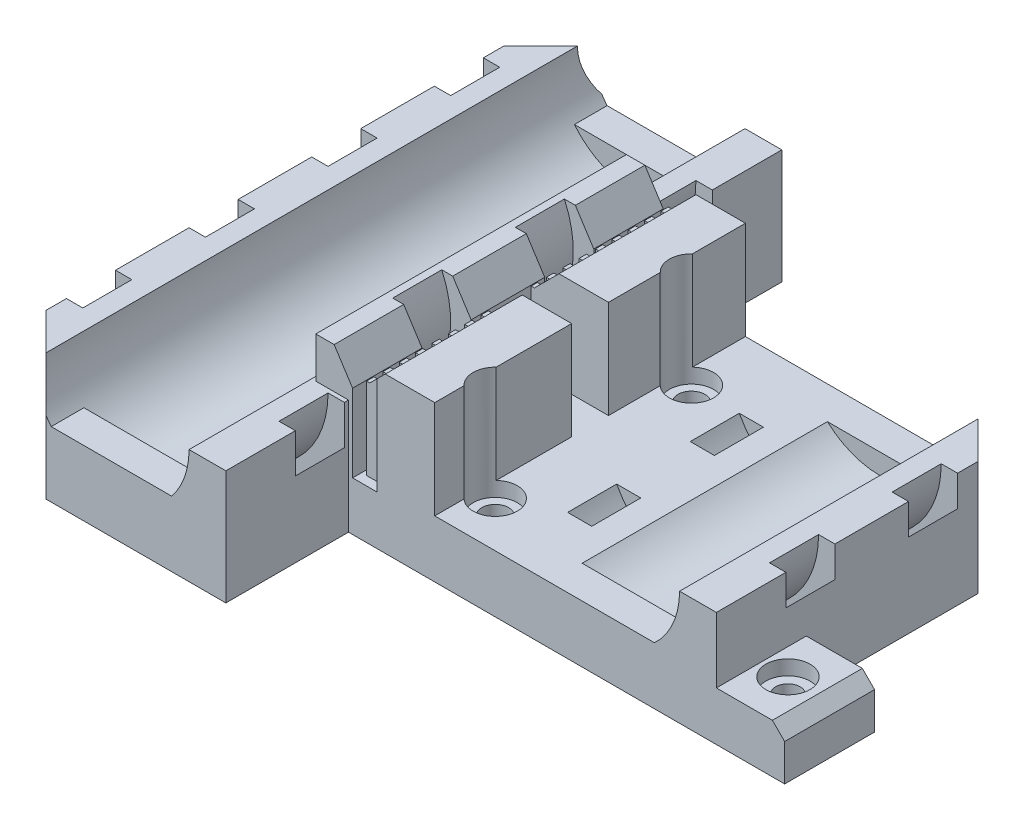
SolidWorks part; units mm, degrees
ref_plane "Front Plane" through (0, 0, 0) normal (0, 0, 1) x (1, 0, 0)
ref_plane "Top Plane" through (0, 0, 0) normal (0, 1, 0) x (1, 0, 0)
ref_plane "Right Plane" through (0, 0, 0) normal (1, 0, 0) x (0, 0, -1)
sketch "Sketch1" plane through (0, 0, 0) normal (0, 1, 0) x (1, 0, 0)
  line L0 (0.3879, -8.2154) -> (0.3879, 6.7846)
  line L1 (-27.6121, -8.2154) -> (0.3879, -8.2154)
  line L2 (-27.6121, -8.2154) -> (-27.6121, 59.7846)
  line L3 (-27.6121, 59.7846) -> (0.3879, 59.7846)
  line L4 (0.3879, 6.7846) -> (53.7379, 6.7846)
  line L5 (53.7379, 6.7846) -> (53.7379, 17.7846)
  line L6 (45.3879, 44.7846) -> (0.3879, 44.7846)
  line L7 (0.3879, 44.7846) -> (0.3879, 59.7846)
  line L8 (53.7379, 17.7846) -> (45.3879, 17.7846)
  line L9 (45.3879, 44.7846) -> (45.3879, 17.7846)
  circle A0 centre (12.7879, 36.3346) radius 1.65
  circle A1 centre (12.7879, 12.3346) radius 1.65
  circle A2 centre (48.5879, 12.3346) radius 1.5
  dimension "D10" = 3.3
  dimension "D13" = 3.3
  dimension "D15" = 3
  dimension "D1" = 68
  dimension "D2" = 28
  dimension "D3" = 15
  dimension "D4" = 15
  dimension "D5" = 53.35
  dimension "D6" = 28
  dimension "D7" = 45
  dimension "D8" = 11
  dimension "D9" = 24
  dimension "D11" = 40.4
  dimension "D12" = 40.4
  dimension "D14" = 8.45
  dimension "D16" = 32.45
  dimension "D17" = 35.8
extrude "Boss-Extrude1" add sketch "Sketch1" along normal blind 19
sketch "Sketch2" plane through (0, 19, 0) normal (0, 1, 0) x (1, 0, 0)
  line L1 (-27.6121, 59.7846) -> (0.3879, 59.7846)
  line L2 (-27.6121, 59.7846) -> (-27.6121, -8.2154)
  line L3 (-27.6121, -8.2154) -> (0.3879, -8.2154)
  line L4 (0.3879, 59.7846) -> (0.3879, -8.2154)
extrude "Cut-Extrude1" cut sketch "Sketch2" against normal blind 5
sketch "Sketch3" plane through (0, 0, 8.2154) normal (0, 0, 1) x (1, 0, 0)
  line L1 (-27.6121, 14) -> (0.3879, 14) construction
  line L2 (0.3879, 14) -> (0.3879, 0) construction
  circle A0 centre (-13.6121, 14) radius 9.5
  dimension "D2" = 19
  dimension "D1" = 0
  dimension "D3" = 14
extrude "Cut-Extrude2" cut sketch "Sketch3" against normal blind 79.7876
sketch "Sketch4" plane through (0, 0, 0) normal (0, -1, 0) x (1, 0, 0)
  line L0 (0.3879, 8.2154) -> (0.3879, -6.7846) construction
  line L1 (-27.6121, 8.2154) -> (0.3879, 8.2154)
  line L2 (-27.6121, 8.2154) -> (-27.6121, 4.2154)
  line L3 (-27.6121, 4.2154) -> (0.3879, 4.2154)
  line L4 (0.3879, 8.2154) -> (0.3879, 4.2154)
  line L5 (0.3879, -44.7846) -> (0.3879, -59.7846) construction
  line L6 (-27.6121, -59.7846) -> (0.3879, -59.7846)
  line L7 (-27.6121, -59.7846) -> (-27.6121, -55.7846)
  line L8 (-27.6121, -55.7846) -> (0.3879, -55.7846)
  line L9 (0.3879, -59.7846) -> (0.3879, -55.7846)
  dimension "D1" = 4
  dimension "D2" = 4
extrude "Boss-Extrude3" add sketch "Sketch4" against normal blind 8
sketch "Sketch5" plane through (0, 14, 0) normal (0, 1, 0) x (1, 0, 0)
  line L0 (-23.1121, 59.7846) -> (-23.1121, -8.2154) construction
  line L1 (-25.6121, 0.2846) -> (-28.4121, 0.2846)
  line L2 (-25.6121, 0.2846) -> (-25.6121, 6.2846)
  line L3 (-25.6121, 6.2846) -> (-28.4121, 6.2846)
  line L4 (-28.4121, 0.2846) -> (-28.4121, 6.2846)
  line L5 (-20.9776, -4.2154) -> (-6.2466, -4.2154) construction
  dimension "D1" = 6
  dimension "D2" = 2.8
  dimension "D3" = 2.5
  dimension "D4" = 4.5
ref_axis "Axis1" through (-13.6121, 14, -59.7846) along (0, 0, 1)
revolve "Cut-Revolve2" cut sketch "Sketch5" angle 360 about axis through (-13.6121, 14, -59.7846) along (0, 0, 1)
sketch "Sketch7" plane through (0, 14, 0) normal (0, 1, 0) x (1, 0, 0)
  line L0 (0.3879, 44.7846) -> (0.3879, 6.7846)
  line L1 (0.3879, 44.7846) -> (-3.6121, 44.7846)
  line L2 (0.3879, 6.7846) -> (-3.6121, 6.7846)
  line L3 (-3.6121, 44.7846) -> (-3.6121, 6.7846)
  dimension "D1" = 4
extrude "Boss-Extrude4" add sketch "Sketch7" along normal blind 5
sketch "Sketch8" plane through (0, 19, 0) normal (0, 1, 0) x (1, 0, 0)
  line L0 (-3.6121, 6.7846) -> (53.7379, 6.7846) construction
  line L1 (0.8879, 6.7846) -> (1.4879, 6.7846)
  line L2 (0.8879, 6.7846) -> (0.8879, 44.7846)
  line L3 (0.8879, 44.7846) -> (1.4879, 44.7846)
  line L4 (1.4879, 6.7846) -> (1.4879, 44.7846)
  line L5 (45.3879, 44.7846) -> (-3.6121, 44.7846) construction
  line L6 (0.3879, 44.7846) -> (0.3879, 59.7846) construction
  dimension "D1" = 0.5
  dimension "D2" = 0.6
extrude "Cut-Extrude3" cut sketch "Sketch8" against normal blind 13
pattern_linear "LPattern1" count 4 spacing 15 along (0, 0, -1) of "Cut-Revolve2"
sketch "Sketch9" plane through (0, 0, -6.7846) normal (0, 0, 1) x (1, 0, 0)
  line L0 (0.8879, 19) -> (-1.3621, 19)
  line L1 (0.8879, 6) -> (0.8879, 19) construction
  line L2 (-3.6121, 19) -> (0.8879, 19) construction
  line L3 (-1.3621, 19) -> (0.8879, 15.5)
  line L4 (0.8879, 15.5) -> (0.8879, 19)
extrude "Cut-Extrude4" cut sketch "Sketch9" against normal blind 54
sketch "Sketch11" plane through (0, 0, -6.7846) normal (0, 0, 1) x (1, 0, 0)
  line L0 (0.3879, 0) -> (53.7379, 0) construction
  circle A0 centre (31.3879, 14) radius 9.5
  dimension "D1" = 19
  dimension "D2" = 45
  dimension "D3" = 14
extrude "Cut-Extrude6" cut sketch "Sketch11" along direction (0, 0, -1) on the side against the normal offset from surface (75 mm away) 75
ref_axis "Axis2" through (31.3879, 14, -44.7846) along (0, 0, 1)
sketch "Sketch12" plane through (0, 19, 0) normal (0, 1, 0) x (1, 0, 0)
  line L0 (23.3101, 44.7846) -> (1.4879, 44.7846) construction
  line L1 (10.9379, 44.7846) -> (31.3879, 44.7846)
  line L2 (10.9379, 44.7846) -> (10.9379, 6.7846)
  line L3 (10.9379, 6.7846) -> (31.3879, 6.7846)
  line L4 (31.3879, 44.7846) -> (31.3879, 6.7846)
  line L5 (31.3879, 44.7846) -> (31.3879, 6.7846) construction
  line L6 (1.4879, 6.7846) -> (1.4879, 44.7846) construction
  dimension "D1" = 0
  dimension "D2" = 9.45
extrude "Cut-Extrude7" cut sketch "Sketch12" against normal blind 12
sketch "Sketch14" plane through (0, 19, 0) normal (0, 1, 0) x (1, 0, 0)
  line L1 (39.4656, 44.7846) -> (53.7379, 44.7846)
  line L2 (39.4656, 44.7846) -> (39.4656, 6.7846)
  line L3 (39.4656, 6.7846) -> (53.7379, 6.7846)
  line L4 (53.7379, 44.7846) -> (53.7379, 6.7846)
extrude "Cut-Extrude9" cut sketch "Sketch14" against normal blind 5
sketch "Sketch15" plane through (0, 14, 0) normal (0, 1, 0) x (1, 0, 0)
  line L0 (40.8879, 6.7846) -> (53.7379, 6.7846) construction
  line L1 (53.7379, 17.7846) -> (45.3879, 17.7846)
  line L2 (53.7379, 17.7846) -> (53.7379, 6.7846)
  line L3 (53.7379, 6.7846) -> (45.3879, 6.7846)
  line L4 (45.3879, 17.7846) -> (45.3879, 6.7846)
extrude "Cut-Extrude10" cut sketch "Sketch15" against normal blind 8
sketch "Sketch16" plane through (0, 0, 0) normal (0, -1, 0) x (-1, 0, 0)
  line L0 (-0.3879, 6.7846) -> (-53.7379, 6.7846) construction
  line L1 (-44.6036, 6.7846) -> (-16.2094, 6.7846)
  line L2 (-44.6036, 6.7846) -> (-44.6036, 10.7846)
  line L3 (-44.6036, 10.7846) -> (-16.2094, 10.7846)
  line L4 (-16.2094, 6.7846) -> (-16.2094, 10.7846)
  line L6 (-45.3879, 44.7846) -> (-21.7206, 44.7846)
  line L7 (-45.3879, 44.7846) -> (-45.3879, 40.7846)
  line L8 (-45.3879, 40.7846) -> (-21.7206, 40.7846)
  line L9 (-21.7206, 44.7846) -> (-21.7206, 40.7846)
  dimension "D1" = 4
  dimension "D2" = 4
extrude "Boss-Extrude5" add sketch "Sketch16" against normal blind 7
sketch "Sketch17" plane through (0, 14, 0) normal (0, 1, 0) x (1, 0, 0)
  line L0 (40.8879, 44.7846) -> (40.8879, 6.7846) construction
  line L1 (43.3879, 21.2846) -> (45.8879, 21.2846)
  line L2 (43.3879, 21.2846) -> (43.3879, 15.2846)
  line L3 (43.3879, 15.2846) -> (45.8879, 15.2846)
  line L4 (45.8879, 21.2846) -> (45.8879, 15.2846)
  line L5 (24.9653, 10.7846) -> (37.8105, 10.7846) construction
  dimension "D1" = 2.5
  dimension "D2" = 6
  dimension "D3" = 2.5
  dimension "D4" = 4.5
revolve "Cut-Revolve3" cut sketch "Sketch17" angle 360 about axis through (31.3879, 14, -44.7846) along (0, 0, 1)
pattern_linear "LPattern2" count 2 spacing 15 along (0, 0, -1) of "Cut-Revolve3"
sketch "Sketch18" plane through (0, 6, 0) normal (0, 1, 0) x (1, 0, 0)
  circle A0 centre (48.5879, 12.3346) radius 2.7
  dimension "D1" = 5.4
extrude "Cut-Extrude11" cut sketch "Sketch18" against normal blind 1.8
sketch "Sketch19" plane through (0, 7, 0) normal (0, 1, 0) x (1, 0, 0)
  circle A0 centre (12.7879, 36.3346) radius 2.7
  circle A1 centre (12.7879, 12.3346) radius 2.7
  dimension "D1" = 5.4
  dimension "D2" = 5.4
extrude "Cut-Extrude12" cut sketch "Sketch19" against normal blind 13.8 from offset 12
sketch "Sketch20" plane through (0, 19, 0) normal (0, 1, 0) x (1, 0, 0)
  line L0 (1.4879, 6.7846) -> (1.4879, 44.7846) construction
  line L1 (3.8879, 42.7846) -> (1.4879, 42.7846)
  line L2 (3.8879, 42.7846) -> (3.8879, 43.8946)
  line L3 (3.8879, 43.8946) -> (1.4879, 43.8946)
  line L4 (1.4879, 42.7846) -> (1.4879, 43.8946)
  line L5 (10.9379, 44.7846) -> (1.4879, 44.7846) construction
  dimension "D1" = 1.11
  dimension "D2" = 2.4
  dimension "D3" = 0.89
extrude "Cut-Extrude13" cut sketch "Sketch20" against normal up to surface (13 mm away) up to face at (1.1879, 6, -25.7846)
pattern_linear "LPattern3" count 20 spacing 2 along (0, 0, 1) of "Cut-Extrude13"
sketch "Sketch23" plane through (0, 0, -6.7846) normal (0, 0, 1) x (1, 0, 0)
  line L1 (10.9379, 19) -> (1.2977, 19)
  line L2 (10.9379, 19) -> (10.9379, 7)
  line L3 (10.9379, 7) -> (1.2977, 7)
  line L4 (1.2977, 19) -> (1.2977, 7)
extrude "Cut-Extrude15" cut sketch "Sketch23" against normal mid plane 4.5 from offset 19 offset against normal yes
chamfer "Chamfer2" distance 1.5 angle 45 1 edges at (53.7379, 6, -12.2846)
chamfer "Chamfer3" distance 6 angle 45 3 edges at (45.3879, 7, -44.7846) (-27.6121, 7, -59.7846) (-27.6121, 7, 8.2154)
sketch "Sketch24" plane through (0, 0, -44.7846) normal (0, 0, -1) x (-1, 0, 0)
  line L0 (-1.4879, 19) -> (-1.4879, 16)
  line L1 (-1.4879, 6) -> (-1.4879, 19) construction
  line L2 (-1.4879, 16) -> (-1.8879, 16)
  line L3 (-1.8879, 16) -> (-4.8879, 19)
  line L4 (-10.9379, 19) -> (-1.4879, 19) construction
  line L5 (-4.8879, 19) -> (-1.4879, 19)
  dimension "D1" = 3
  dimension "D2" = 0.4
extrude "Cut-Extrude16" cut sketch "Sketch24" against normal blind 56
